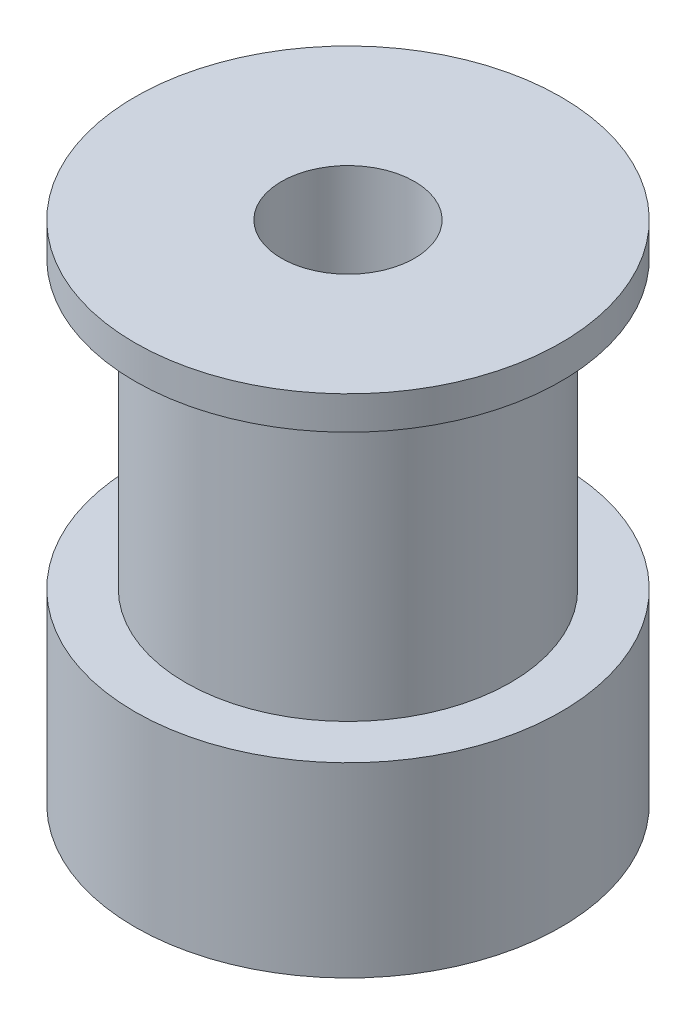
SolidWorks part; units mm, degrees
ref_plane "Front Plane" through (0, 0, 0) normal (0, 0, 1) x (1, 0, 0)
ref_plane "Top Plane" through (0, 0, 0) normal (0, 1, 0) x (1, 0, 0)
ref_plane "Right Plane" through (0, 0, 0) normal (1, 0, 0) x (0, 0, -1)
sketch "Sketch1" plane through (0, 0, 0) normal (0, 0, 1) x (1, 0, 0)
  line L0 (0, 0) -> (0, 19) construction
  line L1 (2.5, 0) -> (2.5, 19)
  line L2 (2.5, 19) -> (8, 19)
  line L3 (8, 19) -> (8, 17.75)
  line L4 (8, 17.75) -> (6.1, 17.75)
  line L5 (6.1, 17.75) -> (6.1, 7)
  line L6 (6.1, 7) -> (8, 7)
  line L7 (8, 7) -> (8, 0)
  line L8 (8, 0) -> (2.5, 0)
  dimension "D1" = 19
  dimension "D2" = 5
  dimension "D3" = 16
  dimension "D4" = 12.2
  dimension "D5" = 1.25
  dimension "D6" = 7
revolve "Revolve1" add sketch "Sketch1" angle 360 about L0
ref_plane "belt_mid_plane" through (0, 12.375, 0) normal (0, -1, 0) x (-1, 0, 0)
